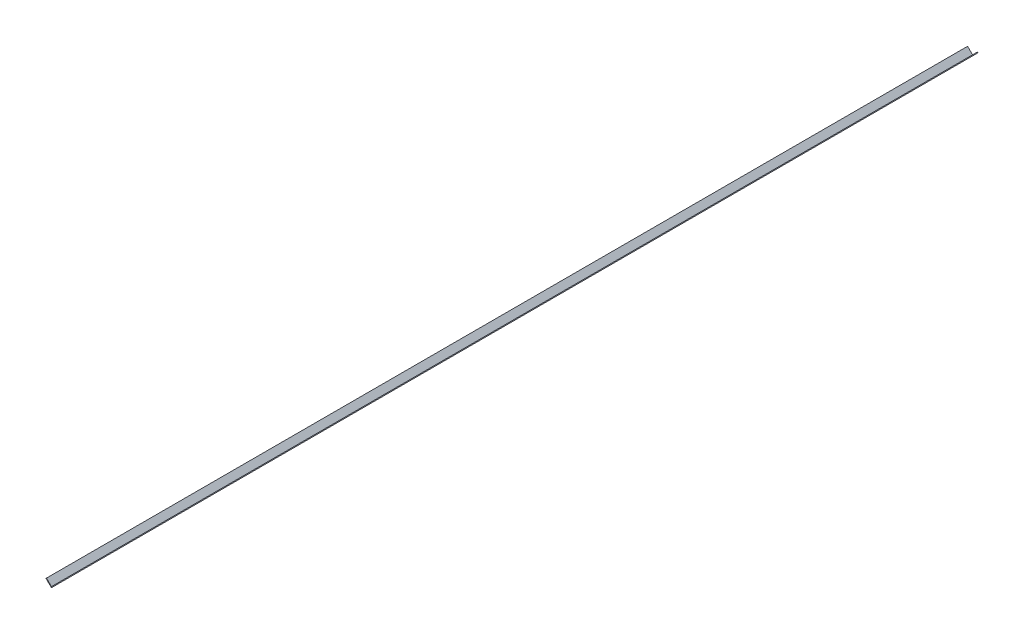
SolidWorks part; units mm, degrees
material "6061 Alloy"
ref_plane "Front Plane" through (0, 0, 0) normal (0, 0, 1) x (1, 0, 0)
ref_plane "Top Plane" through (0, 0, 0) normal (0, 1, 0) x (1, 0, 0)
ref_plane "Right Plane" through (0, 0, 0) normal (1, 0, 0) x (0, 0, -1)
sketch "Sketch1" plane through (0, 0, 0) normal (0, 0, 1) x (1, 0, 0)
  line L0 (0, 0) -> (-8.9803, 8.9803)
  line L1 (-8.9803, 8.9803) -> (-9.8783, 8.0822)
  line L2 (-9.8783, 8.0822) -> (0, -1.7961)
  line L3 (0, -1.7961) -> (9.8783, 8.0822)
  line L4 (9.8783, 8.0822) -> (8.9803, 8.9803)
  line L5 (8.9803, 8.9803) -> (0, 0)
  line L6 (-13.872, 0) -> (16.6117, 0) construction
  point P9 (0, 0)
  dimension "D1" = 1.27
  dimension "D2" = 12.7
extrude "Boss-Extrude1" add sketch "Sketch1" along normal blind 1600.2 and the other way blind 76.2
